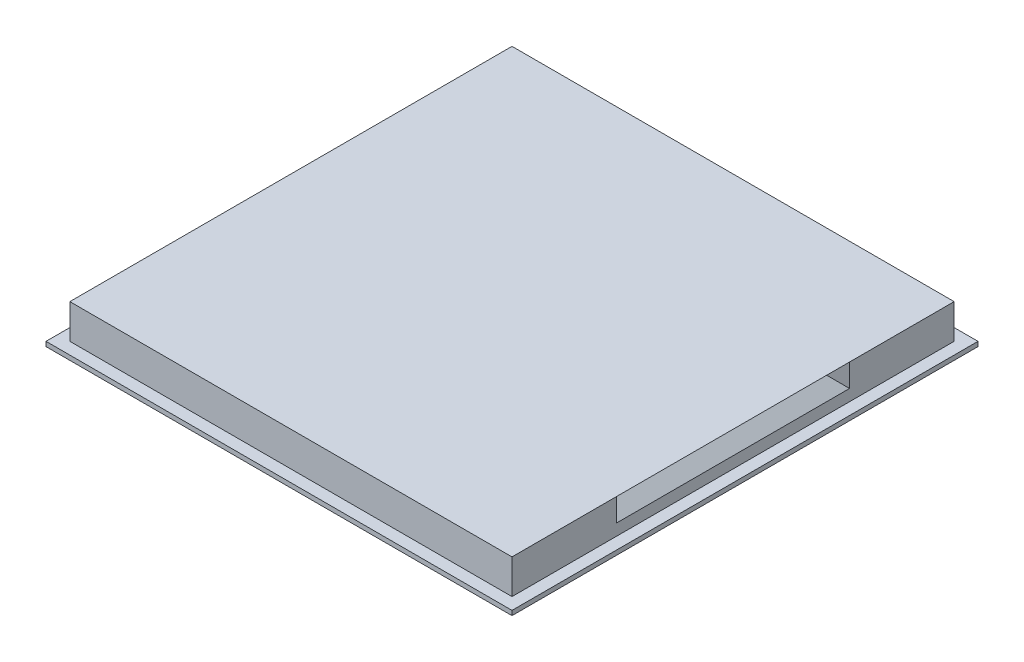
SolidWorks part; units mm, degrees
ref_plane "Front Plane" through (0, 0, 0) normal (0, 0, 1) x (1, 0, 0)
ref_plane "Top Plane" through (0, 0, 0) normal (0, 1, 0) x (1, 0, 0)
ref_plane "Right Plane" through (0, 0, 0) normal (1, 0, 0) x (0, 0, -1)
sketch "Sketch1" plane through (0, 0, 0) normal (0, 1, 0) x (1, 0, 0)
  line L1 (-109.0939, 58.2477) -> (94.1061, 58.2477)
  line L2 (-109.0939, 58.2477) -> (-109.0939, -144.9523)
  line L3 (-109.0939, -144.9523) -> (94.1061, -144.9523)
  line L4 (94.1061, 58.2477) -> (94.1061, -144.9523)
  line L5 (-7.4939, -144.9523) -> (-7.4939, 58.2477) construction
  line L6 (-109.0939, -43.3523) -> (94.1061, -43.3523) construction
  point P68 (-7.4939, -43.3523)
  dimension "D1" = 203.2
  dimension "D2" = 203.2
extrude "Boss-Extrude1" add sketch "Sketch1" along normal blind 2
sketch "Sketch2" plane through (0, 2, 0) normal (0, 1, 0) x (1, 0, 0)
  line L0 (94.1061, -43.3523) -> (88.9061, -43.3523) construction
  line L1 (-103.8939, 53.0477) -> (88.9061, 53.0477)
  line L2 (-103.8939, 53.0477) -> (-103.8939, -139.7523)
  line L3 (-103.8939, -139.7523) -> (88.9061, -139.7523)
  line L4 (88.9061, 53.0477) -> (88.9061, -139.7523)
  line L5 (-7.4939, -139.7523) -> (-7.4939, 53.0477) construction
  line L6 (-103.8939, -43.3523) -> (88.9061, -43.3523) construction
  line L8 (88.9061, -43.3523) -> (-103.8939, -43.3523) construction
  line L9 (-103.8939, -43.3523) -> (-109.0939, -43.3523) construction
  line L10 (-109.0939, 58.2477) -> (-109.0939, -144.9523) construction
  line L11 (-7.4939, 58.2477) -> (-7.4939, 53.0477) construction
  line L12 (94.1061, 58.2477) -> (-109.0939, 58.2477) construction
  line L13 (-7.4939, 53.0477) -> (-7.4939, -139.7523) construction
  line L14 (-7.4939, -139.7523) -> (-7.4939, -144.9523) construction
  line L15 (-109.0939, -144.9523) -> (94.1061, -144.9523) construction
  point P312 (-7.4939, -43.3523)
  dimension "D1" = 5.2
  dimension "D2" = 5.2
  dimension "D3" = 5.2
extrude "Boss-Extrude2" add sketch "Sketch2" along normal blind 15
sketch "Sketch3" plane through (-103.8939, 0, 0) normal (-1, 0, 0) x (0, 0, 1)
  line L0 (-53.0477, 17) -> (139.7523, 17) construction
  line L1 (-7.4477, 17) -> (94.1523, 17)
  line L2 (-7.4477, 17) -> (-7.4477, 7)
  line L3 (-7.4477, 7) -> (94.1523, 7)
  line L4 (94.1523, 17) -> (94.1523, 7)
  line L5 (43.3523, 7) -> (43.3523, 17) construction
  line L6 (-7.4477, 12) -> (94.1523, 12) construction
  point P6 (43.3523, 17)
  point P248 (43.3523, 12)
  dimension "D1" = 10
  dimension "D2" = 101.6
extrude "Cut-Extrude1" cut sketch "Sketch3" against normal blind 6 draft 45
ref_plane "Plane1" through (-7.4939, 0, 0) normal (-1, 0, 0) x (0, 0, 1)
mirror "Mirror1" about plane through (-7.4939, 0, 0) normal (-1, 0, 0) of "Cut-Extrude1"
